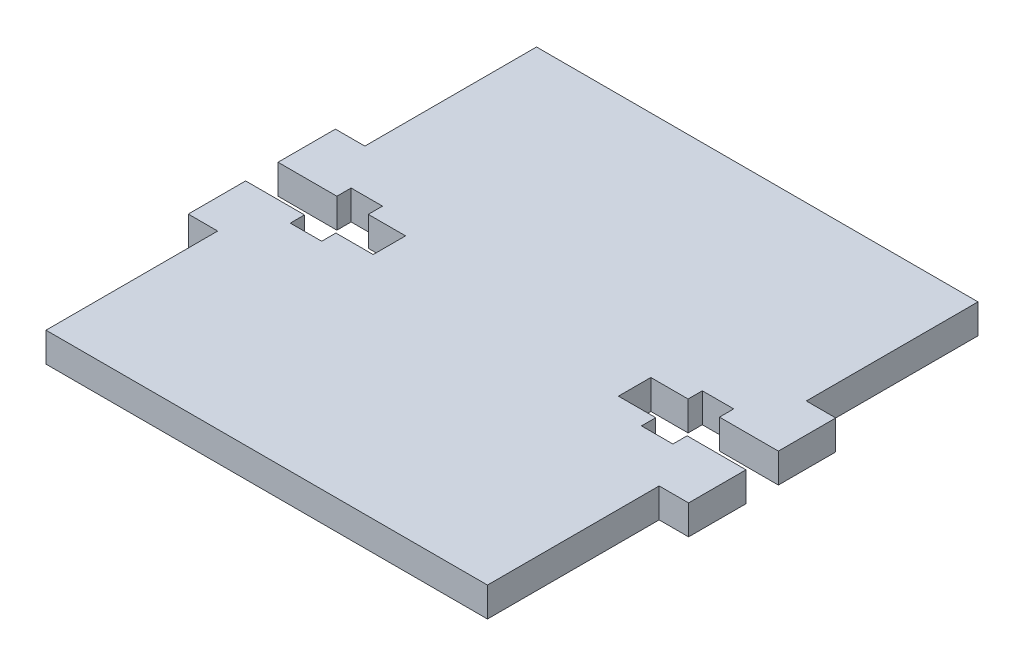
SolidWorks part; units mm, degrees
material "Thornel Mat VMA"
ref_plane "前视基准面" through (0, 0, 0) normal (0, 0, 1) x (1, 0, 0)
ref_plane "上视基准面" through (0, 0, 0) normal (0, 1, 0) x (1, 0, 0)
ref_plane "右视基准面" through (0, 0, 0) normal (1, 0, 0) x (0, 0, -1)
other "Configuration Table"
sketch "草图1" plane through (0, 0, 0) normal (0, 1, 0) x (1, 0, 0)
  line L0 (0, 9.8635) -> (0, -4.0571) construction
  line L1 (-22.5, 25) -> (22.5, 25)
  line L2 (-22.5, 25) -> (-22.5, -25)
  line L3 (-22.5, -25) -> (22.5, -25)
  line L4 (22.5, 25) -> (22.5, -25)
  line L5 (-22.5, 25) -> (22.5, -25) construction
  line L6 (-22.5, -25) -> (22.5, 25) construction
  line L7 (22.5, 7.5) -> (25.5, 7.5)
  line L8 (22.5, 7.5) -> (22.5, -7.5)
  line L9 (22.5, -7.5) -> (25.5, -7.5)
  line L10 (25.5, 7.5) -> (25.5, -7.5)
  line L11 (-22.5, -7.5) -> (-25.5, -7.5)
  line L12 (-25.5, 7.5) -> (-25.5, -7.5)
  line L13 (-22.5, 7.5) -> (-25.5, 7.5)
  line L14 (-22.5, 7.5) -> (-22.5, -7.5)
  point P0 (0, 0)
  point P10 (25.5, 0)
  dimension "D1" = 50
  dimension "D2" = 45
  dimension "D3" = 3
  dimension "D4" = 15
extrude "凸台-拉伸1" add sketch "草图1" along normal mid plane 3 contours L4 L1 L2 L3 | L2 L13 L12 L11 | L10 L7 L4 L9
sketch "草图2" plane through (0, 1.5, 0) normal (0, 1, 0) x (1, 0, 0)
  line L0 (25.5, 7.5) -> (25.5, -7.5) construction
  line L1 (12.5, 1.65) -> (38.5, 1.65)
  line L2 (12.5, 1.65) -> (12.5, -1.65)
  line L3 (12.5, -1.65) -> (38.5, -1.65)
  line L4 (38.5, 1.65) -> (38.5, -1.65)
  line L5 (12.5, 1.65) -> (38.5, -1.65) construction
  line L6 (12.5, -1.65) -> (38.5, 1.65) construction
  line L7 (25.5, 0) -> (17.9, 0) construction
  line L9 (16.3, 3.1) -> (19.5, 3.1)
  line L10 (16.3, 3.1) -> (16.3, -3.1)
  line L11 (16.3, -3.1) -> (19.5, -3.1)
  line L12 (19.5, 3.1) -> (19.5, -3.1)
  line L13 (16.3, 3.1) -> (19.5, -3.1) construction
  line L14 (16.3, -3.1) -> (19.5, 3.1) construction
  point P0 (25.5, 0)
  line M13 (25.5, -7.5) -> (25.5, 7.5)
  dimension "D1" = 3.3
  dimension "D2" = 26
  dimension "D3" = 3.2
  dimension "D4" = 6
  dimension "D5" = 6.2
extrude "切除-拉伸1" cut sketch "草图2" against normal through all both and the other way through all contours L10 L1 L2 L3 | L12 L9 L10 L1 | L12 L1 L10 L3 | L12 L3 L10 L11 | L1 L12 L3 M13
mirror "镜向1" about plane through (0, 0, 0) normal (1, 0, 0) of "切除-拉伸1"
